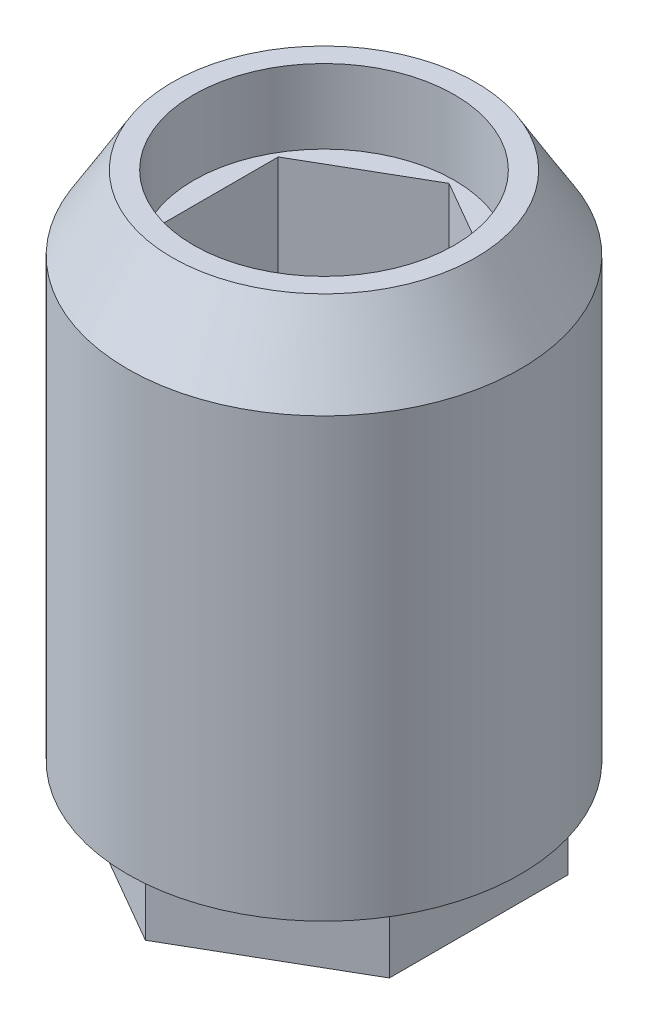
SolidWorks part; units mm, degrees
ref_plane "Спереди" through (0, 0, 0) normal (0, 0, 1) x (1, 0, 0)
ref_plane "Сверху" through (0, 0, 0) normal (0, 1, 0) x (1, 0, 0)
ref_plane "Справа" through (0, 0, 0) normal (1, 0, 0) x (0, 0, -1)
sketch "Эскиз1" plane through (0, 0, 0) normal (0, 1, 0) x (1, 0, 0)
  circle A0 centre (0, 0) radius 8.5
  dimension "D1" = 17
ref_plane "Плоскость4" through (0, -4.15, 0) normal (0, 1, 0) x (1, 0, 0)
sketch "Эскиз2" plane through (0, -4.15, 0) normal (0, 1, 0) x (1, 0, 0)
  circle A0 centre (0, 0) radius 11
  dimension "D1" = 22
ref_plane "Плоскость5" through (0, -28.65, 0) normal (0, 1, 0) x (1, 0, 0)
sketch "Эскиз4" plane through (0, -28.65, 0) normal (0, 1, 0) x (1, 0, 0)
  circle A0 centre (0, 0) radius 11
  dimension "D1" = 22
sketch "Эскиз5" plane through (0, -28.65, 0) normal (0, 1, 0) x (1, 0, 0)
  line L1 (0, 10) -> (-8.6603, 5)
  line L2 (-8.6603, 5) -> (-8.6603, -5)
  line L3 (-8.6603, -5) -> (0, -10)
  line L4 (0, -10) -> (8.6603, -5)
  line L5 (8.6603, -5) -> (8.6603, 5)
  line L6 (8.6603, 5) -> (0, 10)
  circle A0 centre (0, 0) radius 8.6603 construction
  dimension "D1" = 10
ref_plane "Плоскость6" through (0, -32.35, 0) normal (0, 1, 0) x (1, 0, 0)
sketch "Эскиз7" plane through (0, -32.35, 0) normal (0, 1, 0) x (1, 0, 0)
  line L1 (0, 10) -> (-8.6603, 5)
  line L2 (-8.6603, 5) -> (-8.6603, -5)
  line L3 (-8.6603, -5) -> (0, -10)
  line L4 (0, -10) -> (8.6603, -5)
  line L5 (8.6603, -5) -> (8.6603, 5)
  line L6 (8.6603, 5) -> (0, 10)
  circle A0 centre (0, 0) radius 8.6603 construction
  dimension "D1" = 10
loft "По сечениям1" add profiles "Эскиз1", "Эскиз2"
loft "По сечениям2" add profiles "Эскиз4" section edge at (0, -4.15, 11) section "Эскиз4"
cosmetic thread "Условное изображение резьбы6" parameters "D2"=19.252
loft "По сечениям3" add profiles "Эскиз5", "Эскиз7"
sketch "Эскиз8" plane through (0, -32.35, 0) normal (0, -1, 0) x (1, 0, 0)
  line L0 (0, -10) -> (-8.6603, -5) construction
  line L1 (-6.0622, 3.5) -> (-6.0622, -3.5)
  line L2 (-6.0622, -3.5) -> (0, -7)
  line L3 (0, -7) -> (6.0622, -3.5)
  line L4 (6.0622, -3.5) -> (6.0622, 3.5)
  line L5 (6.0622, 3.5) -> (0, 7)
  line L6 (0, 7) -> (-6.0622, 3.5)
  circle A0 centre (0, 0) radius 6.0622 construction
  dimension "D1" = 7
extrude "Вырез-Вытянуть1" cut sketch "Эскиз8" against normal through all
ref_plane "Плоскость7" through (0, -12, 0) normal (0, 1, 0) x (1, 0, 0)
ref_plane "Плоскость8" through (0, -20.35, 0) normal (0, 1, 0) x (1, 0, 0)
sketch "Эскиз9" plane through (0, -20.35, 0) normal (0, 1, 0) x (1, 0, 0)
  circle A0 centre (0, 0) radius 7
sketch "Эскиз10" plane through (0, -12, 0) normal (0, 1, 0) x (1, 0, 0)
  circle A0 centre (0, 0) radius 7 construction
  circle A1 centre (0, 0) radius 7
loft "Вырез-По сечениям1" cut profiles "Эскиз10", "Эскиз9"
sketch "Эскиз12" plane through (0, 0, 0) normal (0, 1, 0) x (1, 0, 0)
  circle A0 centre (0, 0) radius 7.3
  circle A1 centre (0, 0) radius 8.5 construction
  dimension "D1" = 1.2
extrude "Вырез-Вытянуть4" cut sketch "Эскиз12" against normal up to surface (4.15 mm away)
